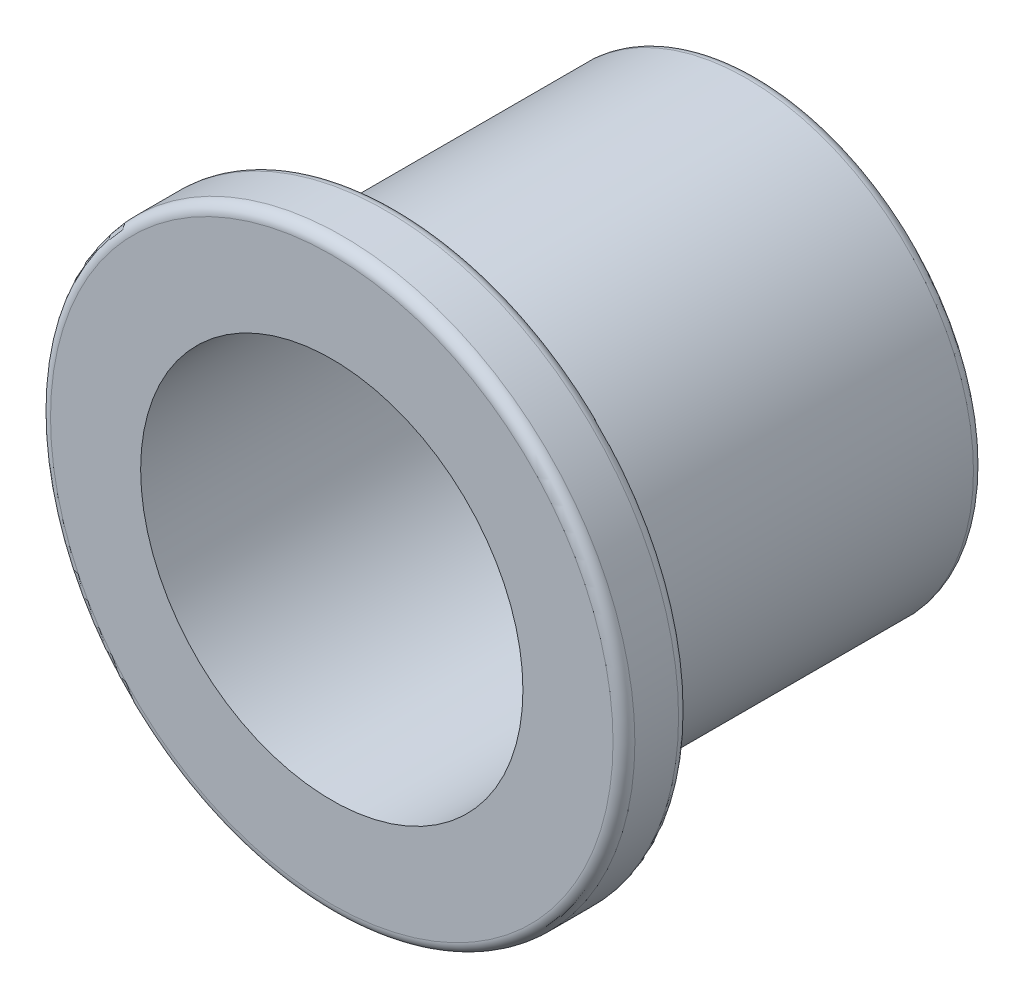
SolidWorks part; units mm, degrees
ref_plane "Alzado" through (0, 0, 0) normal (0, 0, 1) x (1, 0, 0)
ref_plane "Planta" through (0, 0, 0) normal (0, 1, 0) x (1, 0, 0)
ref_plane "Vista lateral" through (0, 0, 0) normal (1, 0, 0) x (0, 0, -1)
sketch "Croquis1" plane through (0, 0, 0) normal (0, 1, 0) x (1, 0, 0)
  line L1 (0, 0) -> (5.35, 0)
  line L2 (0, 0) -> (0, 7.8)
  line L3 (0, 7.8) -> (5.35, 7.8)
  line L4 (5.35, 0) -> (5.35, 7.8)
  dimension "D1" = 7.8
  dimension "D2" = 5.35
revolve "Revolución1" add sketch "Croquis1" angle 360 about L2
sketch "Croquis4" plane through (0, 0, -7.8) normal (0, 0, -1) x (-1, 0, 0)
  circle A0 centre (0, 0) radius 3.5
  dimension "D1" = 7
extrude "Cortar-Extruir1" cut sketch "Croquis4" against normal blind 8 contours A0
sketch "Croquis3" plane through (0, 0, 0) normal (0, 1, 0) x (1, 0, 0)
  line L0 (0, 0) -> (0, 1.2) construction
  line L1 (0, 1.2) -> (0, 7.8) construction
  line L2 (5.35, 7.8) -> (-5.35, 7.8) construction
  line L3 (5.35, 0) -> (5.35, 7.8) construction
  line L5 (5.35, 1.2) -> (4.15, 1.2)
  line L6 (5.35, 1.2) -> (5.35, 7.8)
  line L7 (5.35, 7.8) -> (4.15, 7.8)
  line L8 (4.15, 1.2) -> (4.15, 7.8)
  dimension "D1" = 1.2
  dimension "D2" = 1.2
revolve "Cortar-Revolución1" cut sketch "Croquis3" angle 360 about L1
fillet "Redondeo1" radius 0.2 1 edges at (4.15, 0, -7.8)
fillet "Redondeo2" radius 0.2 1 edges at (4.15, 0, -1.2)
fillet "Redondeo3" radius 0.2 2 edges at (5.35, 0, 0) (5.35, 0, -1.2)
